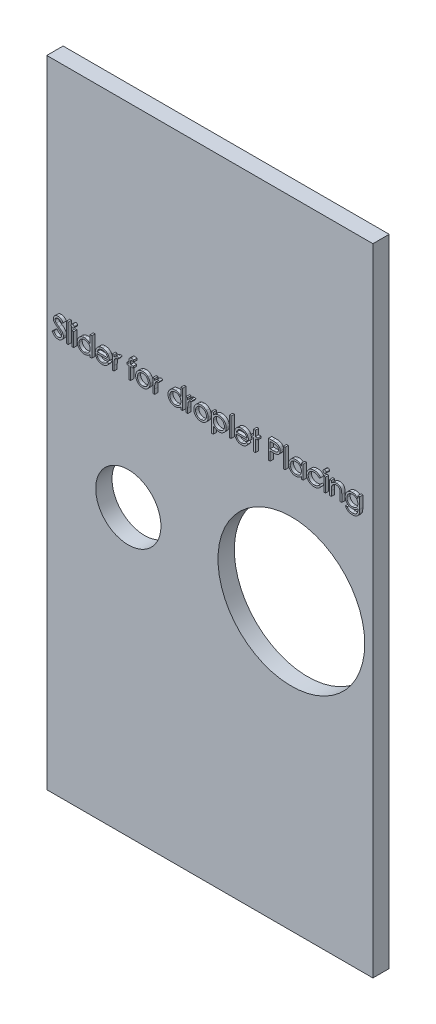
SolidWorks part; units mm, degrees
ref_plane "Front Plane" through (0, 0, 0) normal (0, 0, 1) x (1, 0, 0)
ref_plane "Top Plane" through (0, 0, 0) normal (0, 1, 0) x (1, 0, 0)
ref_plane "Right Plane" through (0, 0, 0) normal (1, 0, 0) x (0, 0, -1)
sketch "Sketch1" plane through (0, 0, 0) normal (0, 0, 1) x (1, 0, 0)
  line L0 (-175.1718, 0) -> (175.1718, 0) construction
  line L1 (0, 0) -> (0, 82.4579) construction
  line L2 (-50, 97.5) -> (-50, -97.5)
  line L3 (50, 97.5) -> (50, -97.5)
  line L4 (-50, 97.5) -> (50, 97.5)
  line L5 (50, -97.5) -> (-50, -97.5)
  line L6 (-38.6042, -10) -> (38.6042, -10) construction
  circle A2 centre (-25, -10) radius 10
  circle A3 centre (25, -10) radius 22.5
  point P4 (0, 0)
  point P10 (-50, 0)
  point P15 (0, -10)
  dimension "D3" = 10
  dimension "D4" = 25
  dimension "D6" = 20
  dimension "D7" = 45
  dimension "D1" = 195
  dimension "D2" = 100
  dimension "D5" = 25
extrude "Boss-Extrude1" add sketch "Sketch1" along normal blind 5
sketch "Sketch2" plane through (0, 0, 5) normal (0, 0, 1) x (1, 0, 0)
  line L0 (0, 0) -> (0, 25) construction
  line L1 (-53.9952, 25) -> (53.9952, 25) construction
  text T0 "Slider for droplet Placing" font "Century Gothic" height in points 22
  point P6 (0, 25)
  point P7 (-53.9952, 25)
  dimension "D1" = 25
extrude "Boss-Extrude2" add sketch "Sketch2" along normal blind 1
